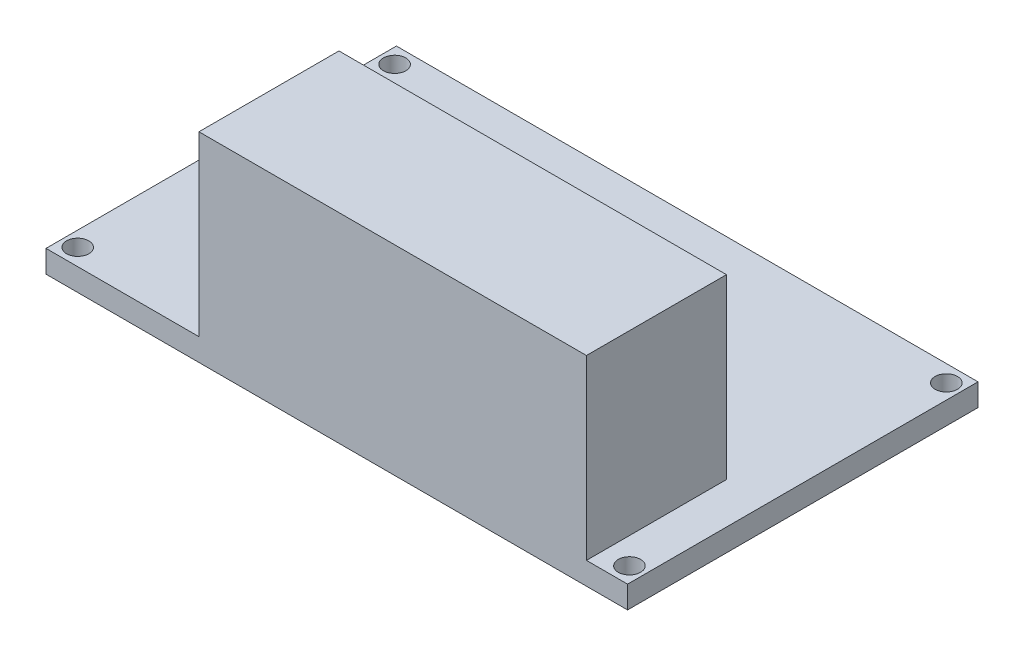
SolidWorks part; units mm, degrees
ref_plane "Front Plane" through (0, 0, 0) normal (0, 0, 1) x (1, 0, 0)
ref_plane "Top Plane" through (0, 0, 0) normal (0, 1, 0) x (1, 0, 0)
ref_plane "Right Plane" through (0, 0, 0) normal (1, 0, 0) x (0, 0, -1)
sketch "Sketch2" plane through (0, 0, 0) normal (0, 1, 0) x (1, 0, 0)
  line L1 (-49.53, -29.845) -> (49.53, -29.845)
  line L2 (-49.53, -29.845) -> (-49.53, 29.845)
  line L3 (-49.53, 29.845) -> (49.53, 29.845)
  line L4 (49.53, -29.845) -> (49.53, 29.845)
  line L5 (-49.53, -29.845) -> (49.53, 29.845) construction
  line L6 (-49.53, 29.845) -> (49.53, -29.845) construction
  point P0 (0, 0)
  dimension "D1" = 59.69
  dimension "D2" = 99.06
extrude "Boss-Extrude1" add sketch "Sketch2" along normal blind 3.81
sketch "Sketch3" plane through (0, 3.81, 0) normal (0, 1, 0) x (1, 0, 0)
  line L1 (46.99, -26.9875) -> (-46.99, -26.9875) construction
  line L2 (46.99, -26.9875) -> (46.99, 26.9875) construction
  line L3 (46.99, 26.9875) -> (-46.99, 26.9875) construction
  line L4 (-46.99, -26.9875) -> (-46.99, 26.9875) construction
  line L5 (46.99, -26.9875) -> (-46.99, 26.9875) construction
  line L6 (46.99, 26.9875) -> (-46.99, -26.9875) construction
  circle A0 centre (-46.99, 26.9875) radius 1.905
  circle A1 centre (46.99, 26.9875) radius 1.905
  circle A2 centre (46.99, -26.9875) radius 1.905
  circle A3 centre (-46.99, -26.9875) radius 1.905
  point P0 (0, 0)
  dimension "D3" = 3.81
  dimension "D1" = 53.975
  dimension "D2" = 93.98
extrude "Cut-Extrude1" cut sketch "Sketch3" against normal through all both and the other way through all
sketch "Sketch4" plane through (0, 3.81, 0) normal (0, 1, 0) x (1, 0, 0)
  line L0 (-49.53, -29.845) -> (49.53, -29.845) construction
  line L1 (42.5256, -29.845) -> (-23.4798, -29.845)
  line L2 (42.5256, -29.845) -> (42.5256, -5.9959)
  line L3 (42.5256, -5.9959) -> (-23.4798, -5.9959)
  line L4 (-23.4798, -29.845) -> (-23.4798, -5.9959)
extrude "Boss-Extrude2" add sketch "Sketch4" along normal blind 30.226
